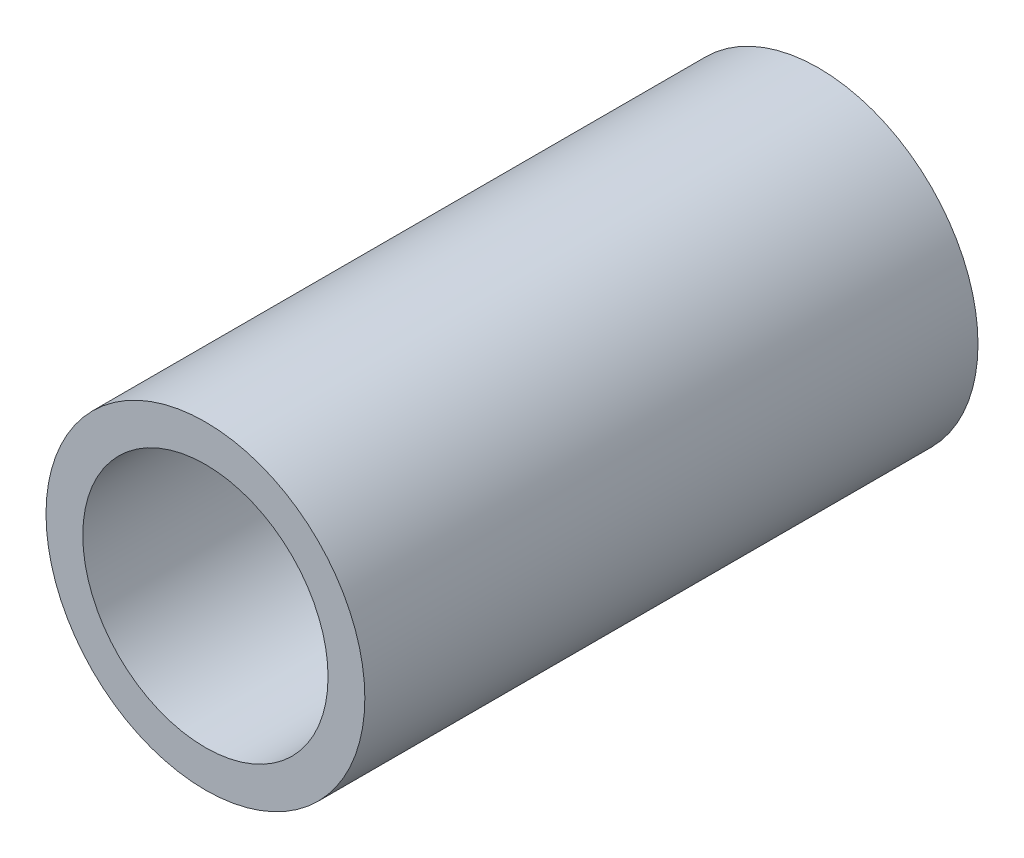
SolidWorks part; units mm, degrees
ref_plane "Front Plane" through (0, 0, 0) normal (0, 0, 1) x (1, 0, 0)
ref_plane "Top Plane" through (0, 0, 0) normal (0, 1, 0) x (1, 0, 0)
ref_plane "Right Plane" through (0, 0, 0) normal (1, 0, 0) x (0, 0, -1)
sketch "Sketch1" plane through (0, 0, 0) normal (0, 0, 1) x (1, 0, 0)
  circle A0 centre (0, 0) radius 16.51
  circle A1 centre (0, 0) radius 12.7
  dimension "D1" = 33.02
  dimension "D2" = 25.4
extrude "Boss-Extrude1" add sketch "Sketch1" along normal blind 63.5
ref_plane "Fitting2" through (0, 0, 63.5) normal (0, 0, 1) x (1, 0, 0)
ref_plane "Fitting1" through (0, 0, 0) normal (0, 0, 1) x (1, 0, 0)
